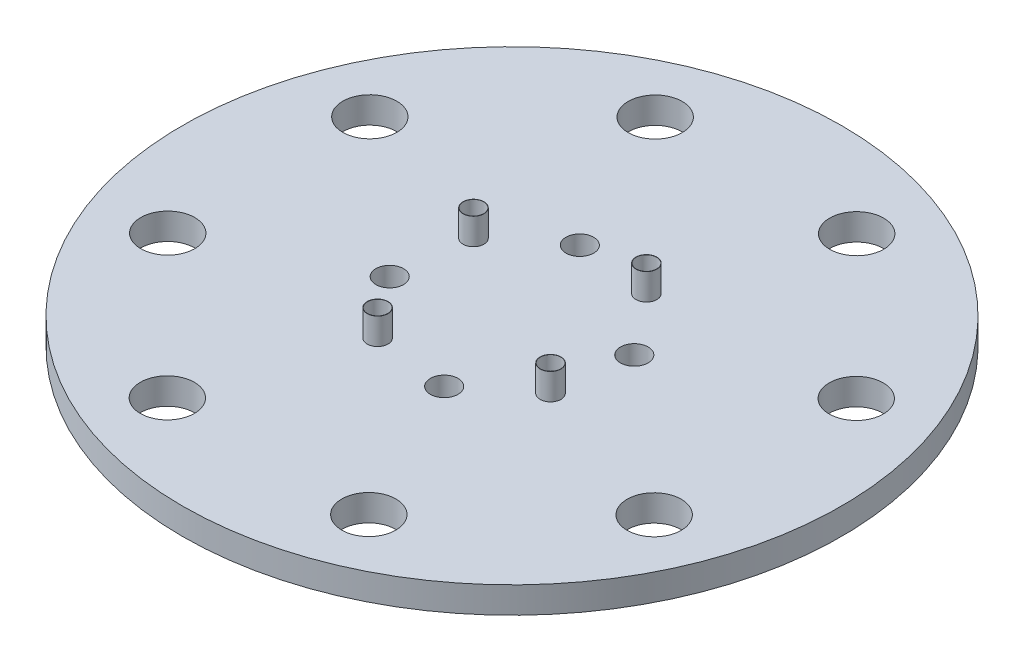
SolidWorks part; units mm, degrees
material "PTFE (general)"
ref_plane "Front Plane" through (0, 0, 0) normal (0, 0, 1) x (1, 0, 0)
ref_plane "Top Plane" through (0, 0, 0) normal (0, 1, 0) x (1, 0, 0)
ref_plane "Right Plane" through (0, 0, 0) normal (1, 0, 0) x (0, 0, -1)
sketch "Sketch1" plane through (0, 0, 0) normal (0, 1, 0) x (1, 0, 0)
  circle A0 centre (0, 0) radius 25
  dimension "D1" = 50
extrude "Boss-Extrude1" add sketch "Sketch1" along normal blind 2
sketch "Sketch2" plane through (0, 2, 0) normal (0, 1, 0) x (1, 0, 0)
  line L0 (0, 0) -> (2.0664, -7.2097) construction
  line L1 (0, 0) -> (-3.6369, -6.5592) construction
  circle A0 centre (0, 0) radius 7.5 construction
  circle A1 centre (-2.0664, 7.2097) radius 1.05
  circle A2 centre (7.2097, 2.0664) radius 1.05
  circle A3 centre (2.0664, -7.2097) radius 1.05
  circle A4 centre (-7.2097, -2.0664) radius 1.05
  circle A9 centre (-3.6369, -6.5592) radius 0.7938
  circle A10 centre (-6.5592, 3.6369) radius 0.7938
  circle A11 centre (3.6369, 6.5592) radius 0.7938
  circle A12 centre (6.5592, -3.6369) radius 0.7938
  point P21 (0, 0)
  point P23 (0, 0)
  dimension "D1" = 15
  dimension "D2" = 2.1
  dimension "D4" = 1.5875
  dimension "D5" = 45
  dimension "D3" = 4
  dimension "D6" = 4
extrude "Cut-Extrude1" cut sketch "Sketch2" against normal through all
sketch "Sketch3" [suppressed] plane through (0, 2, 0) normal (0, 1, 0) x (1, 0, 0)
  circle A0 centre (0, 0) radius 4
  circle A1 centre (0, 0) radius 17.5 construction
  circle A2 centre (17.0562, -3.9161) radius 4
  circle A3 centre (9.2915, -14.8296) radius 4
  circle A4 centre (-3.9161, -17.0562) radius 4
  circle A5 centre (-14.8296, -9.2915) radius 4
  circle A6 centre (-17.0562, 3.9161) radius 4
  circle A7 centre (-9.2915, 14.8296) radius 4
  circle A8 centre (3.9161, 17.0562) radius 4
  circle A9 centre (14.8296, 9.2915) radius 4
  point P23 (0, 0)
  dimension "D1" = 35
  dimension "8" = 8
  dimension "D2" = 8
  dimension "D3" = 8
ref_plane "Plane1" through (0, 0, -25) normal (0, 0, -1) x (-1, 0, 0)
sketch "Sketch4" plane through (0, 0, 0) normal (0, -1, 0) x (1, 0, 0)
  circle A0 centre (0, 0) radius 20 construction
  circle A5 centre (-18.4887, 7.6267) radius 2.05
  circle A6 centre (-18.4887, 7.6267) radius 2.05 construction
  circle A7 centre (-7.6806, 18.4664) radius 2.05
  circle A8 centre (7.6267, 18.4887) radius 2.05
  circle A9 centre (18.4664, 7.6806) radius 2.05
  circle A10 centre (18.4887, -7.6267) radius 2.05
  circle A11 centre (7.6806, -18.4664) radius 2.05
  circle A12 centre (-7.6267, -18.4887) radius 2.05
  circle A13 centre (-18.4664, -7.6806) radius 2.05
  point P31 (0, 0)
  dimension "D1" = 40
  dimension "D2" = 0
  dimension "D4" = 4.1
  dimension "D3" = 8
extrude "Cut-Extrude3" cut sketch "Sketch4" against normal through all
sketch "Sketch6" plane through (0, 0, 0) normal (0, -1, 0) x (1, 0, 0)
  circle A0 centre (20.3384, -6.9714) radius 1.55
  circle A1 centre (0, 0) radius 21.5 construction
  dimension "D1" = 3.1
  dimension "D2" = 43
extrude "Cut-Extrude4" [suppressed] cut sketch "Sketch6" against normal through all
sketch "Sketch7" plane through (0, 0, 0) normal (0, 1, 0) x (1, 0, 0)
  line L0 (0, 0) -> (-38.1181, 0) construction
  line L1 (0, 0) -> (0, -27.4458) construction
  line L2 (-3.6369, -6.5592) -> (-24.4617, -6.5592) construction
  line L3 (6.5592, -3.6369) -> (10.2973, -3.6369) construction
  line L4 (-6.5592, 3.6369) -> (11.0604, 3.6369) construction
  line L5 (3.6369, 6.5592) -> (10.2043, 6.5592) construction
  circle A0 centre (-3.6369, -6.5592) radius 0.7938
  circle A1 centre (-3.6369, -6.5592) radius 0.7738
  circle A2 centre (-6.5592, 3.6369) radius 0.7738
  circle A4 centre (6.5592, -3.6369) radius 0.7938
  circle A5 centre (6.5592, -3.6369) radius 0.7738
  circle A6 centre (-6.5592, 3.6369) radius 0.7938
  circle A7 centre (3.6369, 6.5592) radius 0.7938
  circle A8 centre (3.6369, 6.5592) radius 0.7738
  dimension "D1" = 1.5875
  dimension "D2" = 0.02
  dimension "D6" = 1.5875
  dimension "D7" = 0.02
  dimension "D8" = 1.5875
  dimension "D9" = 0.02
  dimension "D10" = 1.5875
  dimension "D11" = 0.02
  dimension "D3" = 3.6369
  dimension "D4" = 3.6369
  dimension "D5" = 2.9223
extrude "Boss-Extrude2" add sketch "Sketch7" along normal blind 4
